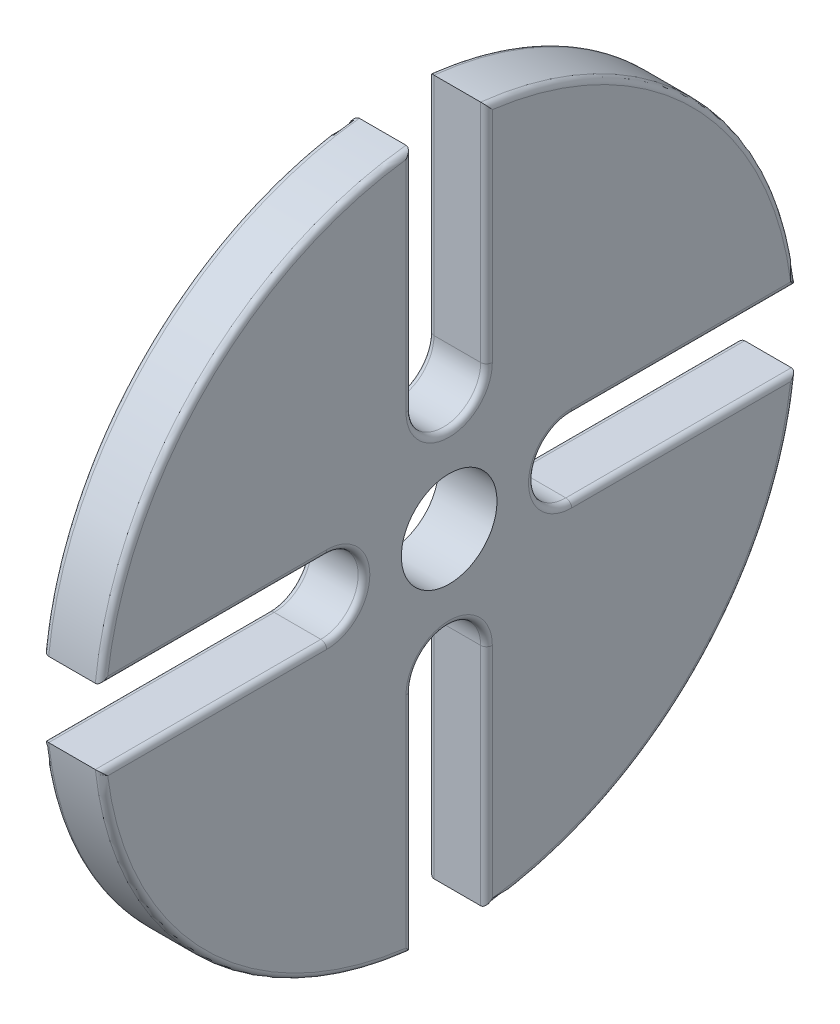
SolidWorks part; units mm, degrees
ref_plane "Front Plane" through (0, 0, 0) normal (0, 0, 1) x (1, 0, 0)
ref_plane "Top Plane" through (0, 0, 0) normal (0, 1, 0) x (1, 0, 0)
ref_plane "Right Plane" through (0, 0, 0) normal (1, 0, 0) x (0, 0, -1)
sketch "Sketch1" plane through (0, 0, 0) normal (1, 0, 0) x (0, 0, -1)
  line L0 (0, 0) -> (0, 30) construction
  line L1 (0, 30) -> (0, 10.5) construction
  line L2 (3.2, 30) -> (3.2, 10.5)
  line L3 (-3.2, 30) -> (-3.2, 10.5)
  line L4 (0, 0) -> (-21.2132, 21.2132)
  line L5 (0, 0) -> (21.2132, 21.2132)
  circle A0 centre (0, 0) radius 30
  circle A1 centre (0, 0) radius 4.1
  arc A2 (3.2, 30) -> (-3.2, 30) centre (0, 30) ccw
  arc A3 (-3.2, 10.5) -> (3.2, 10.5) centre (0, 10.5) ccw
  point P6 (0, 20.25)
  dimension "D1" = 8.2
  dimension "D2" = 60
  dimension "D3" = 6.4
  dimension "D4" = 10.5
  dimension "D5" = 45
extrude "Boss-Extrude1" add sketch "Sketch1" along normal blind 5 contours A3 L3 A0 L4 A1 L5 L2
pattern_circular "CirPattern2" count 4 over 360 about axis through (0, 0, 0) along (1, 0, 0) of "Boss-Extrude1"
fillet "Fillet1" radius 0.5 32 edges at (0, 21.2132, -21.2132) (5, 20.1644, 3.2) (0, 21.2132, 21.2132) (0, 20.1644, 3.2) (0, 7.3, 0) (5, 21.2132, 21.2132) (5, 0, 7.3) (5, -3.2, 20.1644) (0, -21.2132, 21.2132) (0, 3.2, 20.1644) (5, -21.2132, 21.2132) (5, -20.1644, 3.2) (5, -21.2132, -21.2132) (5, -3.2, -20.1644) (5, 3.2, 20.1644) (0, 0, 7.3) (0, 3.2, -20.1644) (0, 0, -7.3) (0, -20.1644, -3.2) (0, -7.3, 0) (0, -3.2, 20.1644) (5, -7.3, 0) (5, -20.1644, -3.2) (0, -21.2132, -21.2132) (0, -20.1644, 3.2) (5, 21.2132, -21.2132) (5, 0, -7.3) (5, 3.2, -20.1644) (0, -3.2, -20.1644) (5, 20.1644, -3.2) (5, 7.3, 0) (0, 20.1644, -3.2)
